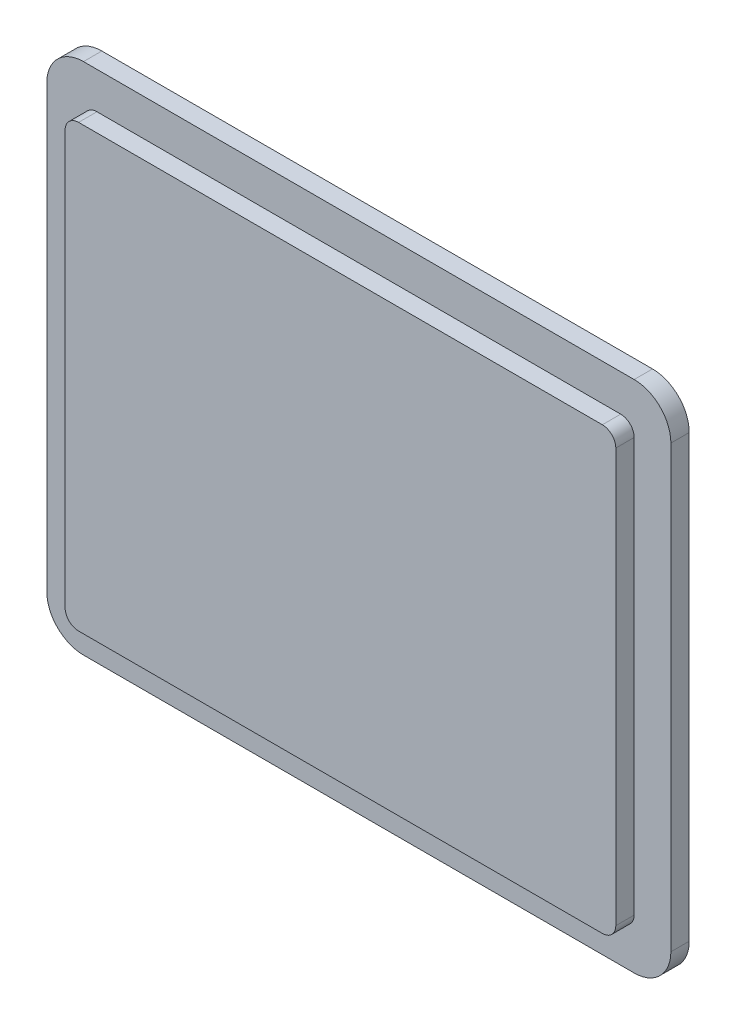
SolidWorks part; units mm, degrees
material "有机玻璃 (TM) GS 丙烯酸铸钣"
ref_plane "前视基准面" through (0, 0, 0) normal (0, 0, 1) x (1, 0, 0)
ref_plane "上视基准面" through (0, 0, 0) normal (0, 1, 0) x (1, 0, 0)
ref_plane "右视基准面" through (0, 0, 0) normal (1, 0, 0) x (0, 0, -1)
sketch "草图1" plane through (0, 0, 0) normal (0, 0, 1) x (1, 0, 0)
  line L1 (3, 0) -> (48, 0)
  line L2 (0, 3) -> (0, 39)
  line L3 (3, 42) -> (48, 42)
  line L4 (51, 3) -> (51, 39)
  arc A0 (48, 0) -> (51, 3) centre (48, 3) ccw
  arc A1 (51, 39) -> (48, 42) centre (48, 39) ccw
  arc A2 (0, 3) -> (3, 0) centre (3, 3) ccw
  arc A3 (0, 39) -> (3, 42) centre (3, 39) cw
  point P7 (51, 0)
  point P12 (0, 0)
  point P15 (0, 42)
  dimension "D3" = 3
  dimension "D1" = 42
  dimension "D2" = 51
extrude "凸台-拉伸1" add sketch "草图1" along normal blind 3
sketch "草图2" plane through (0, 0, 3) normal (0, 0, 1) x (1, 0, 0)
  line L0 (25.5, 42) -> (25.5, -7.7821) construction
  line L1 (4.1, 39) -> (46.9, 39)
  line L2 (3, 37.9) -> (3, 4.1)
  line L3 (4.1, 3) -> (46.9, 3)
  line L4 (48, 37.9) -> (48, 4.1)
  line L5 (48, 42) -> (3, 42) construction
  line L6 (0, 21) -> (61.6132, 21) construction
  line L7 (0, 39) -> (0, 3) construction
  arc A0 (46.9, 39) -> (48, 37.9) centre (46.9, 37.9) cw
  arc A1 (48, 4.1) -> (46.9, 3) centre (46.9, 4.1) cw
  arc A2 (3, 4.1) -> (4.1, 3) centre (4.1, 4.1) ccw
  arc A3 (3, 37.9) -> (4.1, 39) centre (4.1, 37.9) cw
  point P14 (48, 39)
  point P19 (3, 3)
  point P22 (3, 39)
  dimension "D3" = 1.1
  dimension "D1" = 45
  dimension "D2" = 36
extrude "切除-拉伸1" cut sketch "草图2" against normal blind 1.5 flip side to cut
